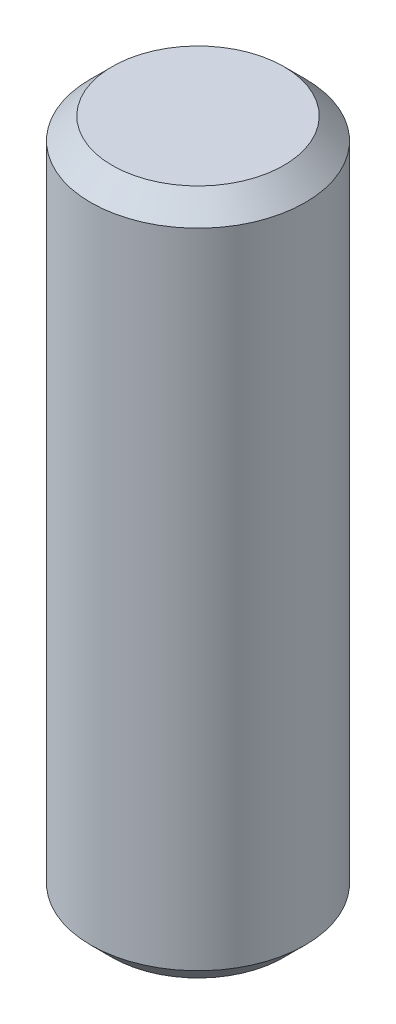
SolidWorks part; units mm, degrees
ref_plane "Front Plane" through (0, 0, 0) normal (0, 0, 1) x (1, 0, 0)
ref_plane "Top Plane" through (0, 0, 0) normal (0, 1, 0) x (1, 0, 0)
ref_plane "Right Plane" through (0, 0, 0) normal (1, 0, 0) x (0, 0, -1)
sketch "Sketch1" plane through (0, 0, 0) normal (0, 1, 0) x (1, 0, 0)
  circle A0 centre (0, 0) radius 2.5
  dimension "D1" = 5
extrude "Boss-Extrude1" add sketch "Sketch1" along normal blind 16
chamfer "Chamfer1" distance 0.5 angle 45 2 edges at (0, 16, 2.5) (0, 0, 2.5)
